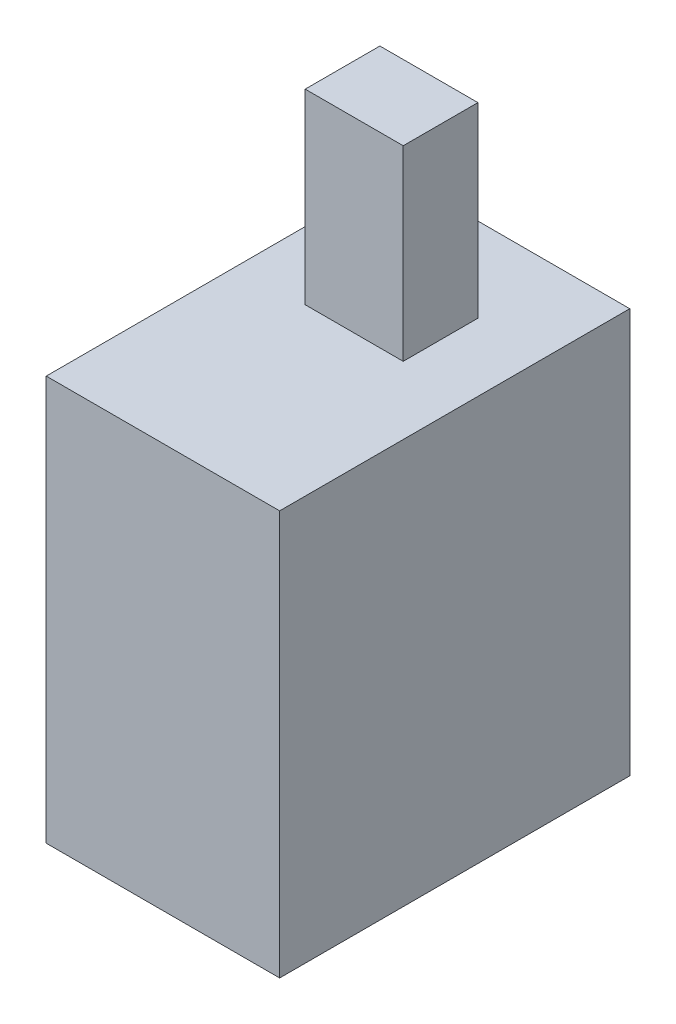
SolidWorks part; units mm, degrees
ref_plane "Alzado" through (0, 0, 0) normal (0, 0, 1) x (1, 0, 0)
ref_plane "Planta" through (0, 0, 0) normal (0, 1, 0) x (1, 0, 0)
ref_plane "Vista lateral" through (0, 0, 0) normal (1, 0, 0) x (0, 0, -1)
sketch "Croquis1" plane through (0, 0, 0) normal (0, 1, 0) x (1, 0, 0)
  line L1 (0, 0) -> (15, 0)
  line L2 (0, 0) -> (0, 22.5)
  line L3 (0, 22.5) -> (15, 22.5)
  line L4 (15, 0) -> (15, 22.5)
  dimension "D1" = 22.5
  dimension "D2" = 15
extrude "Saliente-Extruir1" add sketch "Croquis1" along normal blind 26
sketch "Croquis2" plane through (0, 26, 0) normal (0, 1, 0) x (1, 0, 0)
  line L0 (0, 0) -> (15, 0) construction
  line L1 (4.35, 17.0916) -> (10.65, 17.0916)
  line L2 (4.35, 17.0916) -> (4.35, 12.2916)
  line L3 (4.35, 12.2916) -> (10.65, 12.2916)
  line L4 (10.65, 17.0916) -> (10.65, 12.2916)
  point P4 (7.5, 12.2916)
  point P7 (7.5, 0)
  dimension "D1" = 6.3
  dimension "D2" = 4.8
extrude "Saliente-Extruir2" add sketch "Croquis2" along normal blind 12
